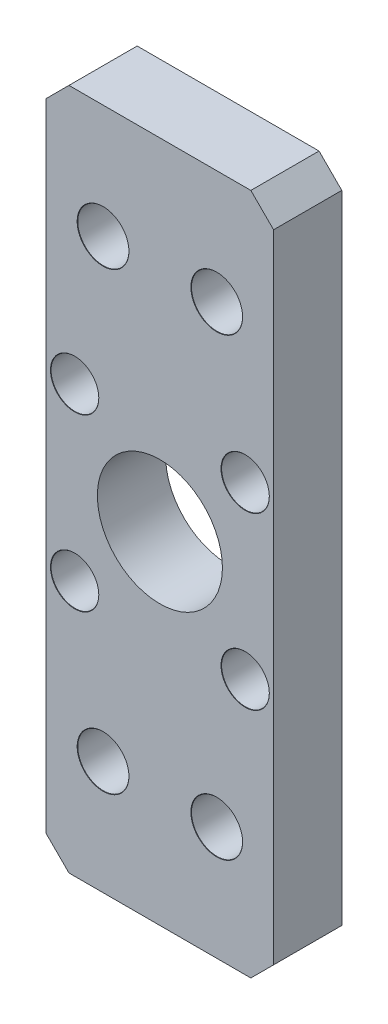
SolidWorks part; units mm, degrees
material "ABS"
ref_plane "前视基准面" through (0, 0, 0) normal (0, 0, 1) x (1, 0, 0)
ref_plane "上视基准面" through (0, 0, 0) normal (0, 1, 0) x (1, 0, 0)
ref_plane "右视基准面" through (0, 0, 0) normal (1, 0, 0) x (0, 0, -1)
other "Configuration Table"
sketch "草图1" plane through (0, 0, 0) normal (0, 0, 1) x (1, 0, 0)
  line L1 (-10, -30) -> (10, -30)
  line L2 (-10, -30) -> (-10, 30)
  line L3 (-10, 30) -> (10, 30)
  line L4 (10, -30) -> (10, 30)
  line L5 (-10, -30) -> (10, 30) construction
  line L6 (-10, 30) -> (10, -30) construction
  point P0 (0, 0)
  dimension "D1" = 20
  dimension "D2" = 60
extrude "凸台-拉伸1" add sketch "草图1" along normal blind 6
sketch "草图2" plane through (0, 0, 6) normal (0, 0, 1) x (1, 0, 0)
  line L0 (10, -30) -> (10, 30) construction
  line L1 (10, 30) -> (-10, 30) construction
  point P0 (-5, 20)
  point P1 (5, 20)
  point P6 (0, 0)
  dimension "D1" = 10
  dimension "D2" = 5
  dimension "D3" = 10
hole_wizard "Ø4.5 (4.5) 直径孔1" positions "3D草图1" profile "草图3" hole size "Ø4.5" standard "GB" end condition through all
sketch3d "3D草图1"
  point P0 (-5, 20, 6)
  point P3 (5, 20, 6)
sketch "草图3" plane through (-5, 20, 6) normal (1, 0, 0) x (0, -1, 0)
  line L0 (0, 0) -> (0, 6)
  line L1 (0, 6) -> (2.25, 6)
  line L2 (2.25, 6) -> (2.25, 0.025)
  line L3 (2.25, 0.025) -> (2.275, 0)
  line L5 (2.275, 0) -> (0, 0)
  line L6 (-2.25, 0.025) -> (-2.275, 0) construction
  line L11 (0, -6.35) -> (0, 107.95) construction
  dimension "通孔孔直径" = 4.5
  dimension "通孔孔深度" = 6
  dimension "近端锥形沉头孔直径" = 4.55
  dimension "近端锥形沉头孔角度" = 90
mirror "镜向1" about plane through (0, 0, 0) normal (0, 1, 0) of "Ø4.5 (4.5) 直径孔1"
sketch "草图4" plane through (0, 0, 6) normal (0, 0, 1) x (1, 0, 0)
  circle A0 centre (0, 0) radius 5.5
  dimension "D1" = 11
extrude "切除-拉伸1" cut sketch "草图4" against normal blind 6
sketch "草图5" plane through (0, 0, 6) normal (0, 0, 1) x (1, 0, 0)
  line L1 (-7.5, -7.5) -> (7.5, -7.5) construction
  line L2 (-7.5, -7.5) -> (-7.5, 7.5) construction
  line L3 (-7.5, 7.5) -> (7.5, 7.5) construction
  line L4 (7.5, -7.5) -> (7.5, 7.5) construction
  line L5 (-7.5, -7.5) -> (7.5, 7.5) construction
  line L6 (-7.5, 7.5) -> (7.5, -7.5) construction
  point P0 (0, 0)
  dimension "D1" = 15
  dimension "D2" = 15
hole_wizard "Ø4.2 (4.2) 直径孔1" positions "3D草图4" profile "草图8" hole size "Ø4.2" standard "GB" end condition through all
sketch3d "3D草图4"
  point P0 (-7.5, 7.5, 6)
  point P3 (7.5, 7.5, 6)
  point P6 (7.5, -7.5, 6)
  point P9 (-7.5, -7.5, 6)
sketch "草图8" plane through (-7.5, 7.5, 6) normal (1, 0, 0) x (0, -1, 0)
  line L0 (0, 0) -> (0, 6)
  line L1 (0, 6) -> (2.1, 6)
  line L2 (2.1, 6) -> (2.1, 0.025)
  line L3 (2.1, 0.025) -> (2.125, 0)
  line L5 (2.125, 0) -> (0, 0)
  line L6 (-2.1, 0.025) -> (-2.125, 0) construction
  line L11 (0, -6.35) -> (0, 107.95) construction
  dimension "通孔孔直径" = 4.2
  dimension "通孔孔深度" = 6
  dimension "近端锥形沉头孔直径" = 4.25
  dimension "近端锥形沉头孔角度" = 90
chamfer "倒角1" distance 2 angle 45 4 edges at (10, -30, 3) (-10, -30, 3) (10, 30, 3) (-10, 30, 3)
